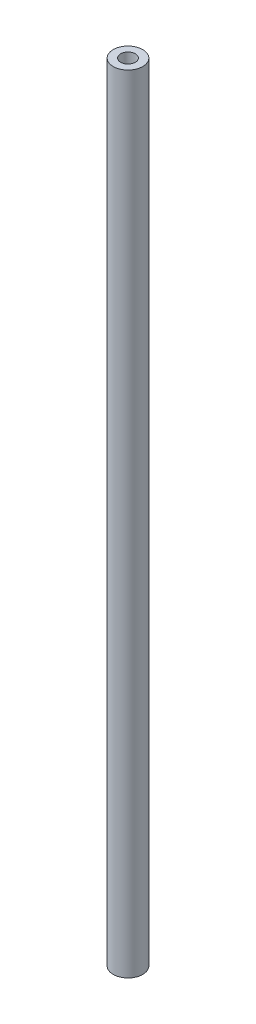
SolidWorks part; units mm, degrees
ref_plane "Front Plane" through (0, 0, 0) normal (0, 0, 1) x (1, 0, 0)
ref_plane "Top Plane" through (0, 0, 0) normal (0, 1, 0) x (1, 0, 0)
ref_plane "Right Plane" through (0, 0, 0) normal (1, 0, 0) x (0, 0, -1)
sketch "Sketch1" plane through (0, 0, 0) normal (0, 1, 0) x (1, 0, 0)
  circle A0 centre (0, 0) radius 1.5
  circle A1 centre (0, 0) radius 3
  dimension "D1" = 3
  dimension "D2" = 6
extrude "Boss-Extrude1" add sketch "Sketch1" along normal blind 160
sketch "Sketch2" plane through (0, 0, 0) normal (0, -1, 0) x (1, 0, 0)
  circle A1 centre (0, 0) radius 3
  circle A2 centre (0, 0) radius 3
  dimension "D1" = 0
extrude "Boss-Extrude2" add sketch "Sketch2" against normal blind 5
